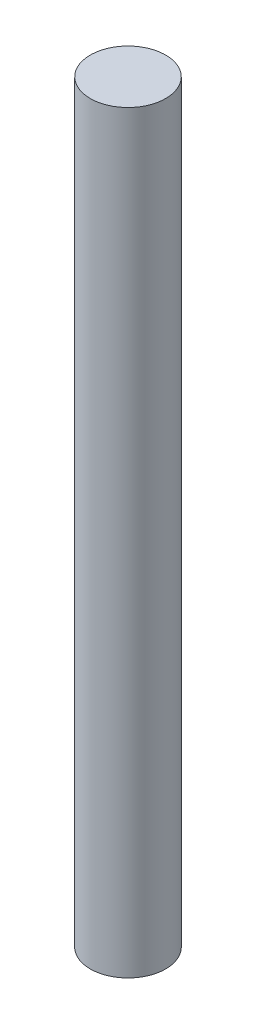
SolidWorks part; units mm, degrees
ref_plane "Front Plane" through (0, 0, 0) normal (0, 0, 1) x (1, 0, 0)
ref_plane "Top Plane" through (0, 0, 0) normal (0, 1, 0) x (1, 0, 0)
ref_plane "Right Plane" through (0, 0, 0) normal (1, 0, 0) x (0, 0, -1)
sketch "Sketch1" plane through (0, 0, 0) normal (0, 1, 0) x (1, 0, 0)
  circle A0 centre (0, 0) radius 2.5
  dimension "D1" = 5
extrude "Boss-Extrude1" add sketch "Sketch1" along normal mid plane 50
